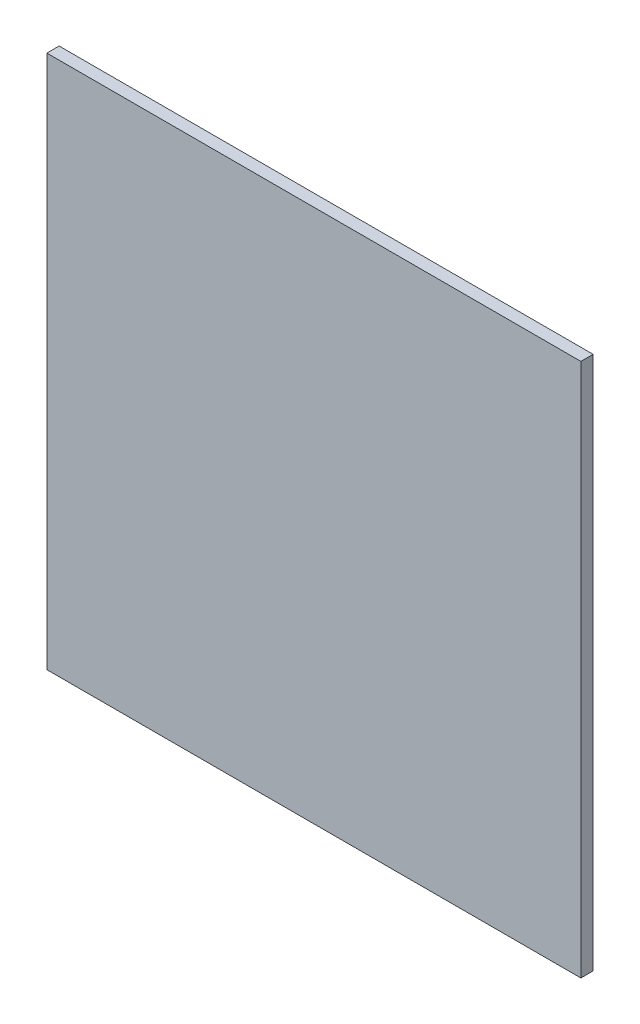
SolidWorks part; units mm, degrees
ref_plane "Ebene vorne" through (0, 0, 0) normal (0, 0, 1) x (1, 0, 0)
ref_plane "Ebene oben" through (0, 0, 0) normal (0, 1, 0) x (1, 0, 0)
ref_plane "Ebene rechts" through (0, 0, 0) normal (1, 0, 0) x (0, 0, -1)
sketch "Skizze1" plane through (0, 0, 0) normal (0, 0, 1) x (1, 0, 0)
  line L1 (-67.5, -67.5) -> (67.5, -67.5)
  line L2 (-67.5, -67.5) -> (-67.5, 67.5)
  line L3 (-67.5, 67.5) -> (67.5, 67.5)
  line L4 (67.5, -67.5) -> (67.5, 67.5)
  line L5 (-67.5, -67.5) -> (67.5, 67.5) construction
  line L6 (-67.5, 67.5) -> (67.5, -67.5) construction
  point P0 (0, 0)
  dimension "D1" = 135
  dimension "D2" = 135
extrude "Aufsatz-Linear austragen1" add sketch "Skizze1" against normal blind 3.1
